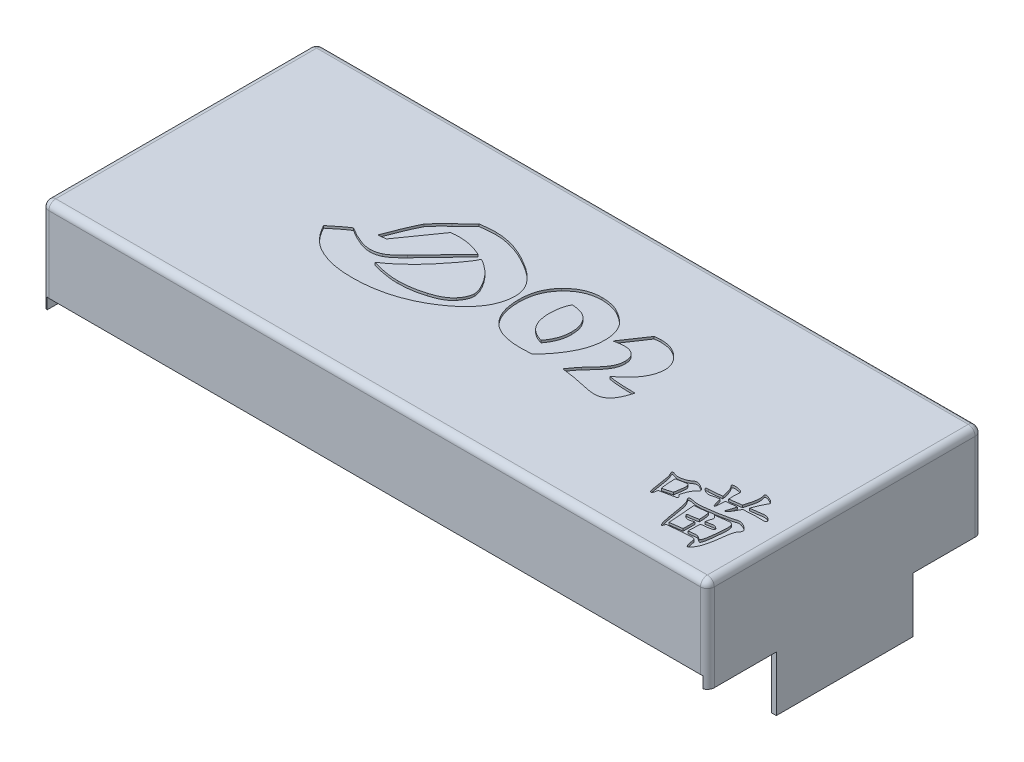
SolidWorks part; units mm, degrees
ref_plane "Front Plane" through (0, 0, 0) normal (0, 0, 1) x (1, 0, 0)
ref_plane "Top Plane" through (0, 0, 0) normal (0, 1, 0) x (1, 0, 0)
ref_plane "Right Plane" through (0, 0, 0) normal (1, 0, 0) x (0, 0, -1)
sketch "Sketch1" plane through (0, 0, 0) normal (0, 1, 0) x (1, 0, 0)
  line L1 (-144.75, -59.75) -> (144.75, -59.75)
  line L2 (-144.75, -59.75) -> (-144.75, 59.75)
  line L3 (-144.75, 59.75) -> (144.75, 59.75)
  line L4 (144.75, -59.75) -> (144.75, 59.75)
  line L5 (-144.75, -59.75) -> (144.75, 59.75) construction
  line L6 (-144.75, 59.75) -> (144.75, -59.75) construction
  point P0 (0, 0)
  dimension "D1" = 289.5
  dimension "D2" = 119.5
extrude "Boss-Extrude1" add sketch "Sketch1" along normal blind 65
shell "Shell1" thickness 2
sketch "Sketch2" plane through (0, 0, 0) normal (0, 0, 1) x (1, 0, 0)
  line L0 (65.725, 0) -> (-65.725, 0) construction
  line L1 (-142.75, 29) -> (142.75, 29)
  line L2 (-142.75, 29) -> (-142.75, 0)
  line L3 (-142.75, 0) -> (142.75, 0)
  line L4 (142.75, 29) -> (142.75, 0)
  line L7 (-144.75, 65) -> (-144.75, 0) construction
  dimension "D1" = 29
  dimension "D2" = 285.5
  dimension "D3" = 2
  dimension "D4" = 0
extrude "Cut-Extrude1" cut sketch "Sketch2" against normal through all both and the other way through all
sketch "Sketch3" plane through (0, 0, 0) normal (1, 0, 0) x (0, 0, -1)
  line L0 (65.725, 0) -> (-65.725, 0) construction
  line L1 (-59.75, 24) -> (-29.75, 24)
  line L2 (-59.75, 24) -> (-59.75, 0)
  line L3 (-59.75, 0) -> (-29.75, 0)
  line L4 (59.75, 24) -> (59.75, 0)
  line L5 (59.75, 65) -> (59.75, 0) construction
  line L6 (29.75, 24) -> (59.75, 24)
  line L8 (-29.75, 24) -> (-29.75, 0)
  line L10 (29.75, 24) -> (29.75, 0)
  line L11 (29.75, 0) -> (59.75, 0)
  dimension "D1" = 30
  dimension "D2" = 30
  dimension "D3" = 24
extrude "Cut-Extrude3" cut sketch "Sketch3" against normal through all both and the other way through all
sketch "Sketch4" plane through (0, 0, 0) normal (1, 0, 0) x (0, 0, -1)
  line L0 (65.725, 0) -> (-65.725, 0) construction
  line L1 (-5, 0) -> (5, 0)
  line L2 (-5, 0) -> (-5, 29)
  line L4 (5, 0) -> (5, 29)
  line L5 (0, 35.75) -> (0, -35.75) construction
  arc A0 (5, 29) -> (-5, 29) centre (0, 29) ccw
  dimension "D1" = 29
  dimension "D2" = 10
  dimension "D3" = 5
  dimension "D4" = 29
extrude "Cut-Extrude4" cut sketch "Sketch4" against normal through all
sketch "Sketch6" plane through (0, 65, 0) normal (0, 1, 0) x (1, 0, 0)
  text T0 "喵" font "KaiTi" height 30
sketch "Sketch7" plane through (0, 65, 0) normal (0, 1, 0) x (1, 0, 0)
  text T0 "D02" font "Matura MT Script Capitals" height 50
extrude "Cut-Extrude5" cut sketch "Sketch7" against normal blind 1
extrude "Cut-Extrude6" cut sketch "Sketch6" against normal blind 1
fillet "Fillet1" radius 3 3 edges at (142.75, 26.5, 59.75) (143.75, 24, 59.75) (144.75, 44.5, 59.75)
fillet "Fillet2" radius 3 3 edges at (142.75, 26.5, -59.75) (144.75, 44.5, -59.75) (143.75, 24, -59.75)
fillet "Fillet3" radius 3 5 edges at (-1.5, 65, 59.75) (144.75, 65, 0) (143.8713, 65, 58.8713) (-1.5, 65, -59.75) (143.8713, 65, -58.8713)
fillet "Fillet4" radius 3 9 edges at (-142.75, 26.5, -59.75) (-142.75, 26.5, 59.75) (-144.75, 43, -59.75) (-144.75, 65, 0) (-144.75, 43, 59.75) (-144.75, 64.1213, 58.8713) (-144.75, 64.1213, -58.8713) (-143.75, 24, 59.75) (-143.75, 24, -59.75)
